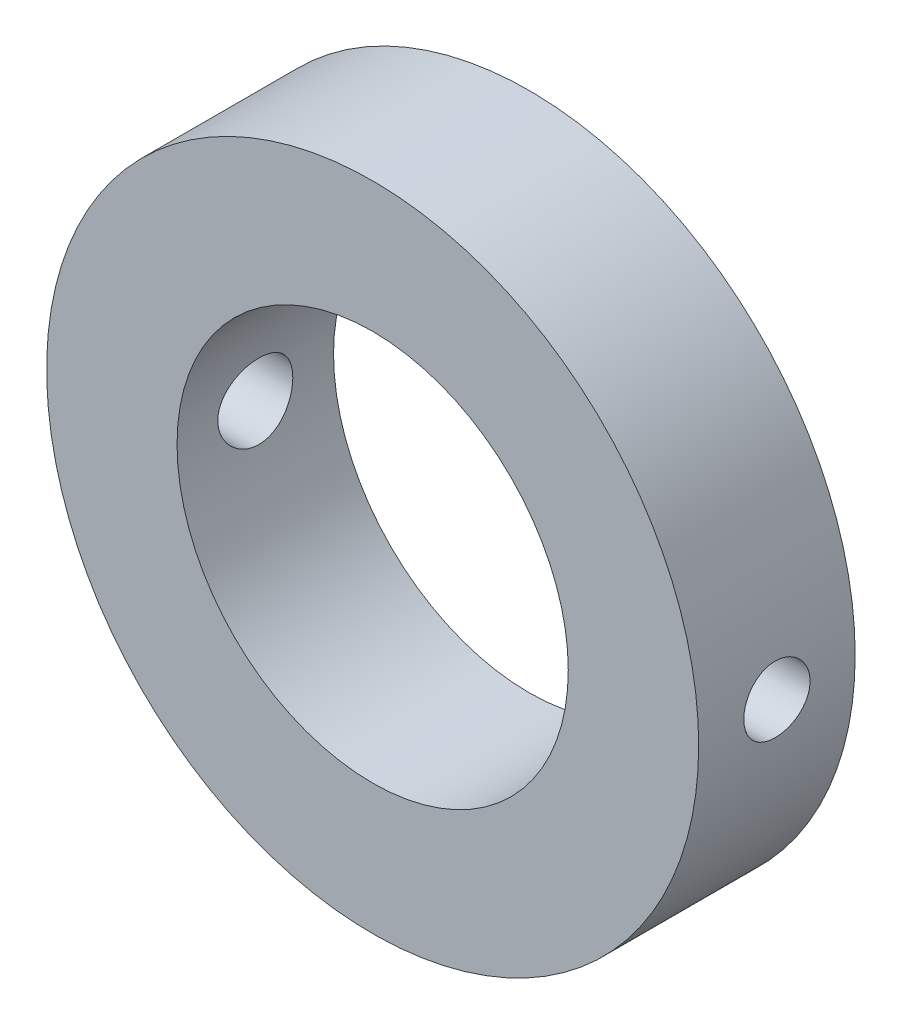
SolidWorks part; units mm, degrees
ref_plane "Front Plane" through (0, 0, 0) normal (0, 0, 1) x (1, 0, 0)
ref_plane "Top Plane" through (0, 0, 0) normal (0, 1, 0) x (1, 0, 0)
ref_plane "Right Plane" through (0, 0, 0) normal (1, 0, 0) x (0, 0, -1)
sketch "Sketch2" plane through (0, 0, 0) normal (0, 0, 1) x (1, 0, 0)
  circle A0 centre (0, 0) radius 15
  circle A1 centre (0, 0) radius 25
  dimension "D1" = 50
  dimension "D2" = 30
extrude "Boss-Extrude1" add sketch "Sketch2" along normal mid plane 12
sketch "Sketch5" plane through (0, 0, 0) normal (0, 0, 1) x (1, 0, 0)
  line L0 (-30, 3) -> (-30, 0)
  line L2 (30, 0) -> (30, 2.5)
  line L3 (30, 2.5) -> (-30, 3)
  line L4 (30, 0) -> (-30, 0)
  point P7 (30, 0)
  point P8 (0, 0)
  point P9 (30, 0)
  point P10 (46.6927, 0)
  dimension "D3" = 60
  dimension "D4" = 30
  dimension "D5" = 2.5
  dimension "D6" = 3
revolve "Cut-Revolve1" cut sketch "Sketch5" angle 360 about L4
